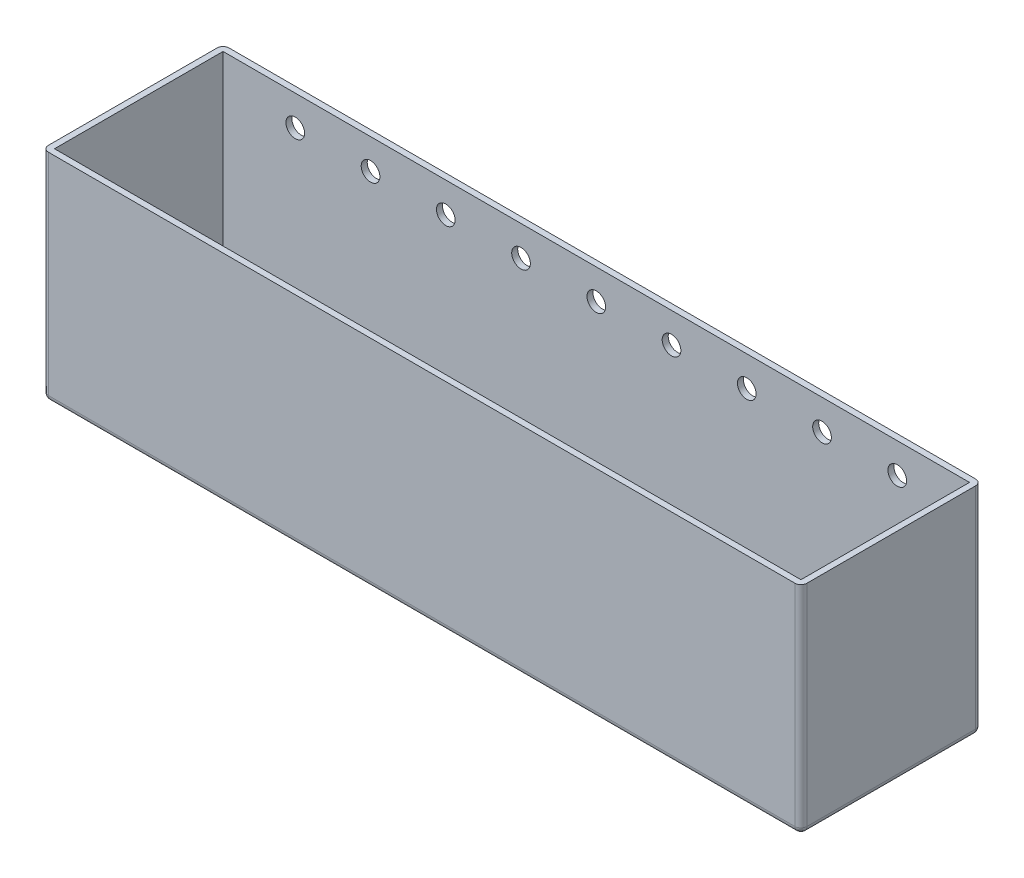
SolidWorks part; units mm, degrees
ref_plane "前视基准面" through (0, 0, 0) normal (0, 0, 1) x (1, 0, 0)
ref_plane "上视基准面" through (0, 0, 0) normal (0, 1, 0) x (1, 0, 0)
ref_plane "右视基准面" through (0, 0, 0) normal (1, 0, 0) x (0, 0, -1)
other "Configuration Table"
sketch "草图1" plane through (0, 0, 0) normal (0, 1, 0) x (1, 0, 0)
  line L0 (-59.1857, 36.9509) -> (66.8143, 36.9509)
  line L1 (66.8143, 36.9509) -> (66.8143, 6.9509)
  line L2 (66.8143, 6.9509) -> (-59.1857, 6.9509)
  line L3 (-59.1857, 6.9509) -> (-59.1857, 36.9509)
  dimension "D1" = 126
  dimension "D2" = 30
extrude "凸台-拉伸1" add sketch "草图1" along normal blind 36
shell "抽壳1" thickness 1
sketch "草图2" plane through (-59.1857, 0, 0) normal (-1, 0, 0) x (0, 0, 1)
  line L0 (-21.9509, 0) -> (-21.9509, 36.4105) construction
  line L1 (-30.9509, 8.5) -> (-12.9509, 8.5)
  line L2 (-12.9509, 0) -> (-12.9509, 8.5)
  line L3 (-30.9509, 0) -> (-30.9509, 8.5)
  line L4 (16.5, 0) -> (-16.5, 0) construction
  line L5 (-30.9509, 0) -> (-12.9509, 0)
  point P9 (-21.9509, 8.5)
  dimension "D1" = 9
  dimension "D2" = 8.5
extrude "切除-拉伸1" cut sketch "草图2" against normal blind 12
sketch "草图4" plane through (0, 0, 0) normal (0, -1, 0) x (1, 0, 0)
  line L0 (-59.1857, -21.9509) -> (67.7911, -21.9509) construction
  line L1 (-59.1857, -12.9509) -> (-59.1857, -30.9509) construction
  circle A0 centre (-13.4473, -21.9509) radius 0.0182
  circle A1 centre (-13.4473, -21.9509) radius 1.55
  circle A2 centre (4.3027, -21.9509) radius 1.55
  circle A3 centre (22.0527, -21.9509) radius 1.55
  circle A4 centre (51.9455, -17.9425) radius 1.55
  circle A5 centre (52.0558, -32.7887) radius 1.55
  point P4 (22.0527, -21.9509)
  point P5 (-13.4473, -21.9509)
  point P8 (4.3027, -21.9509)
  point P14 (52.0527, -21.9509)
  point P15 (52.0527, -17.9509)
  point P16 (52.0527, -32.9509)
  dimension "D3" = 30
  dimension "D1" = 17.75
  dimension "D2" = 17.75
  dimension "D4" = 4
  dimension "D5" = 11
extrude "切除-拉伸2" cut sketch "草图4" against normal blind 12
fillet "圆角1" radius 1 9 edges at (-59.1857, 0, -9.9509) (-59.1857, 0, -33.9509) (-59.1857, 18, -36.9509) (-59.1857, 18, -6.9509) (3.8143, 0, -6.9509) (66.8143, 18, -6.9509) (66.8143, 0, -21.9509) (3.8143, 0, -36.9509) (66.8143, 18, -36.9509)
sketch "草图5" plane through (0, 0, -36.9509) normal (0, 0, -1) x (-1, 0, 0)
  line L0 (-3.8143, 36) -> (-3.8143, -8.8966) construction
  line L2 (-65.8143, 36) -> (58.1857, 36) construction
  line L8 (-53.8143, 36) -> (-53.8143, 31) construction
  line L9 (-53.8143, 31) -> (46.1857, 31) construction
  line L10 (46.1857, 31) -> (46.1857, 36) construction
  circle A0 centre (-28.8143, 31) radius 1.55
  circle A1 centre (-53.8143, 31) radius 1.55
  circle A2 centre (-3.8143, 31) radius 1.55
  circle A3 centre (21.1857, 31) radius 1.55
  circle A4 centre (46.1857, 31) radius 1.55
  circle A5 centre (-41.3143, 31) radius 1.55
  circle A6 centre (-16.3143, 31) radius 1.55
  circle A7 centre (8.6857, 31) radius 1.55
  circle A8 centre (33.6857, 31) radius 1.55
  point P1 (-53.8143, 36)
  point P2 (46.1857, 36)
  point P8 (-3.8143, 31)
  point P11 (-41.3143, 31)
  point P12 (-16.3143, 31)
  point P25 (0, 0)
  dimension "D4" = 37.5
  dimension "D1" = 50
  dimension "D2" = 50
  dimension "D3" = 5
  dimension "D5" = 12.5
extrude "切除-拉伸3" cut sketch "草图5" against normal blind 10
